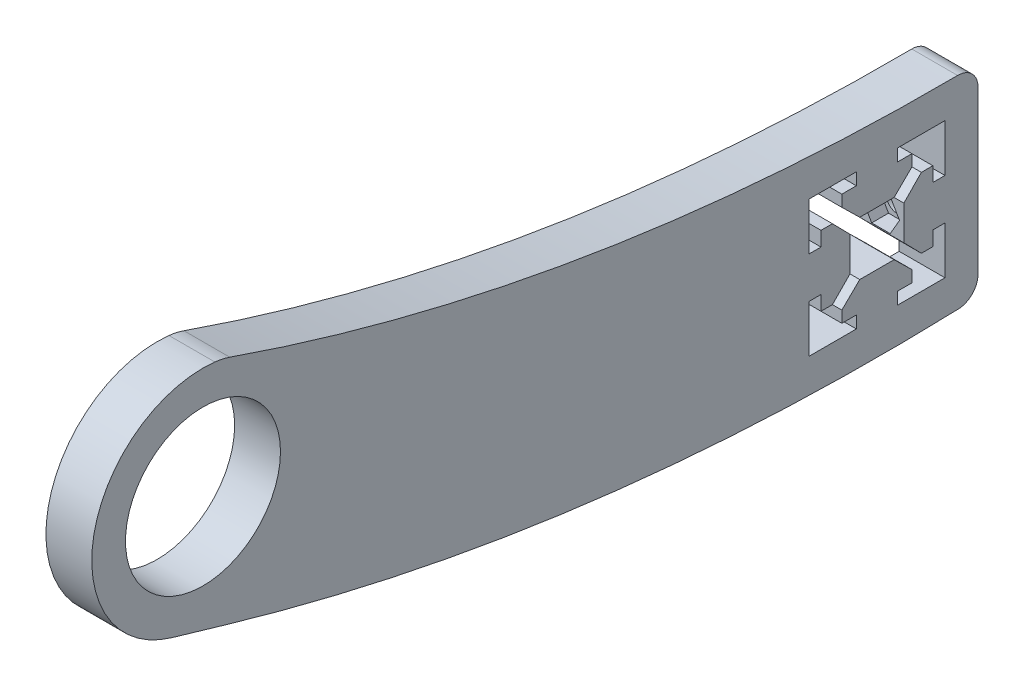
SolidWorks part; units mm, degrees
ref_plane "Front Plane" through (0, 0, 0) normal (0, 0, 1) x (1, 0, 0)
ref_plane "Top Plane" through (0, 0, 0) normal (0, 1, 0) x (1, 0, 0)
ref_plane "Right Plane" through (0, 0, 0) normal (1, 0, 0) x (0, 0, -1)
sketch "Base" plane through (0, 0, 0) normal (1, 0, 0) x (0, 0, -1)
  line L2 (105.2, -10.25) -> (105.2, -8.55)
  line L4 (94.8, -8.55) -> (94.8, -10.25)
  line L5 (97.45, -12.85) -> (102.55, -12.85)
  line L6 (94.8, -10.25) -> (97.45, -12.85)
  line L7 (105.2, -10.25) -> (102.55, -12.85)
  line L8 (94.8, -8.55) -> (96.95, -8.55)
  line L10 (105.2, -8.55) -> (103.05, -8.55)
  line L12 (96.95, -8.55) -> (103.05, -8.55) construction
  line L14 (96.95, -8.55) -> (96.95, -6.75)
  line L16 (103.05, -8.55) -> (103.05, -6.75)
  line L21 (106.6, -22.05) -> (108.3, -22.05)
  line L22 (108.3, -11.65) -> (106.6, -11.65)
  line L23 (104, -14.3) -> (104, -19.4)
  line L24 (106.6, -11.65) -> (104, -14.3)
  line L25 (106.6, -22.05) -> (104, -19.4)
  line L26 (108.3, -11.65) -> (108.3, -13.8)
  line L27 (108.3, -22.05) -> (108.3, -19.9)
  line L28 (108.3, -13.8) -> (110.1, -13.8)
  line L29 (108.3, -19.9) -> (110.1, -19.9)
  line L30 (108.3, -13.8) -> (108.3, -19.9) construction
  line L31 (94.8, -23.45) -> (94.8, -25.15)
  line L32 (105.2, -25.15) -> (105.2, -23.45)
  line L33 (102.55, -20.85) -> (97.45, -20.85)
  line L34 (105.2, -23.45) -> (102.55, -20.85)
  line L35 (94.8, -23.45) -> (97.45, -20.85)
  line L36 (105.2, -25.15) -> (103.05, -25.15)
  line L37 (94.8, -25.15) -> (96.95, -25.15)
  line L38 (103.05, -25.15) -> (103.05, -26.95)
  line L39 (96.95, -25.15) -> (96.95, -26.95)
  line L40 (103.05, -25.15) -> (96.95, -25.15) construction
  line L41 (93.4, -11.65) -> (91.7, -11.65)
  line L42 (91.7, -22.05) -> (93.4, -22.05)
  line L43 (96, -19.4) -> (96, -14.3)
  line L44 (93.4, -22.05) -> (96, -19.4)
  line L45 (93.4, -11.65) -> (96, -14.3)
  line L46 (91.7, -22.05) -> (91.7, -19.9)
  line L47 (91.7, -11.65) -> (91.7, -13.8)
  line L48 (91.7, -19.9) -> (89.9, -19.9)
  line L49 (91.7, -13.8) -> (89.9, -13.8)
  line L50 (91.7, -19.9) -> (91.7, -13.8) construction
  line L51 (103.05, -6.75) -> (110.1, -6.75)
  line L52 (110.1, -6.75) -> (110.1, -13.8)
  line L53 (110.1, -19.9) -> (110.1, -26.95)
  line L54 (110.1, -26.95) -> (103.05, -26.95)
  line L55 (96.95, -26.95) -> (89.9, -26.95)
  line L56 (89.9, -26.95) -> (89.9, -19.9)
  line L57 (89.9, -13.8) -> (89.9, -6.75)
  line L58 (89.9, -6.75) -> (96.95, -6.75)
  line L63 (115, -4.888) -> (115, -28.961)
  circle A0 centre (0, 0) radius 11.5
  circle A1 centre (100, -16.85) radius 2.25 construction
  arc A2 (-4.6329, -15.8362) -> (1.7563, 16.4063) centre (0, 0) cw
  arc A3 (3.9751, 15.9087) -> (111.9763, -1.8881) centre (109.4394, 319.321) ccw
  arc A4 (3.4098, -18.1928) -> (112.1004, -31.9593) centre (100.5556, 312.8462) ccw
  arc A5 (115, -4.888) -> (111.9763, -1.8881) centre (112, -4.888) ccw
  arc A6 (112.1004, -31.9593) -> (115, -28.961) centre (112, -28.961) ccw
  arc A7 (3.9751, 15.9087) -> (1.7563, 16.4063) centre (0.6919, 6.4631) ccw
  arc A8 (3.4098, -18.1928) -> (-4.6329, -15.8362) centre (-2812.4224, -9613.5609) ccw
  point P5 (100, -8.55)
  point P11 (100, -12.85)
  point P36 (100, -16.85)
  point P51 (100, -16.85)
  point P61 (115, -1.85)
  point P64 (115, -31.85)
  dimension "D1" = 100
  dimension "D6" = 4.5
  dimension "D7" = 23
  dimension "D18" = 3
  dimension "D19" = 3
  dimension "D21" = 10
  dimension "D23" = 10000
  dimension "D2" = 16.85
  dimension "D3" = 4
  dimension "D4" = 5.1
  dimension "D5" = 1.7
  dimension "D8" = 2.65
  dimension "D9" = 1.7
  dimension "D10" = 2.6
  dimension "D11" = 2.6
  dimension "D12" = 0
  dimension "D13" = 2.65
  dimension "D14" = 0
  dimension "D15" = 6.1
  dimension "D16" = 10.1
  dimension "D17" = 10.1
  dimension "D20" = 30
  dimension "D22" = 15
extrude "Boss-Extrude1" add sketch "Base" along normal blind 6.8
sketch "Sketch3" plane through (0, 0, -104) normal (0, 0, 1) x (1, 0, 0)
  line L0 (0, -14.3) -> (0, -19.4) construction
  line L1 (0, -19.4) -> (6.8, -19.4) construction
  line L2 (6.8, -19.4) -> (6.8, -14.3) construction
  line L3 (6.8, -14.3) -> (0, -14.3) construction
  line L4 (3.4, -14.3) -> (3.4, -19.4) construction
  line L5 (6.8, -16.85) -> (0, -16.85) construction
  line L7 (6.1536, -16.85) -> (4.7768, -14.4653)
  line L8 (4.7768, -14.4653) -> (2.0232, -14.4653)
  line L9 (2.0232, -14.4653) -> (0.6464, -16.85)
  line L10 (0.6464, -16.85) -> (2.0232, -19.2347)
  line L11 (2.0232, -19.2347) -> (4.7768, -19.2347)
  line L12 (4.7768, -19.2347) -> (6.1536, -16.85)
  circle A0 centre (3.4, -16.85) radius 2.3847 construction
  point P12 (3.4, -16.85)
sketch "Sketch6" plane through (0, 0, -115) normal (0, 0, -1) x (-1, 0, 0)
  point P0 (-3.4, -16.85)
hole_wizard "CSK for M3 Flat Head Machine Screw1" positions "Sketch7" profile "Sketch8" countersink size "M3" standard "ANSI Metric"
sketch "Sketch7" plane through (0, 0, -115) normal (0, 0, -1) x (-1, 0, 0)
  point P0 (-3.4, -16.85)
sketch "Sketch8" plane through (3.4, -16.85, -115) normal (1, 0, 0) x (0, 1, 0)
  line L0 (0, 0) -> (0, 12.0805)
  line L1 (0, 12.0805) -> (1.8, 10.999)
  line L2 (1.8, 10.999) -> (1.8, 1.35)
  line L3 (1.8, 1.35) -> (3.15, 0)
  line L5 (3.15, 0) -> (0, 0)
  line L6 (-1.8, 1.35) -> (-3.15, 0) construction
  line L10 (0, 12.0805) -> (-1.8, 10.999) construction
  line L11 (0, -6.35) -> (0, 107.95) construction
  dimension "Hole Dia." = 3.6
  dimension "Hole Depth" = 10.999
  dimension "Near C'Sink Dia." = 6.3
  dimension "Near C'Sink Angle" = 90
  dimension "Drill Angle" = 118
extrude "Cut-Extrude1" cut sketch "Sketch3" against normal blind 2.5
